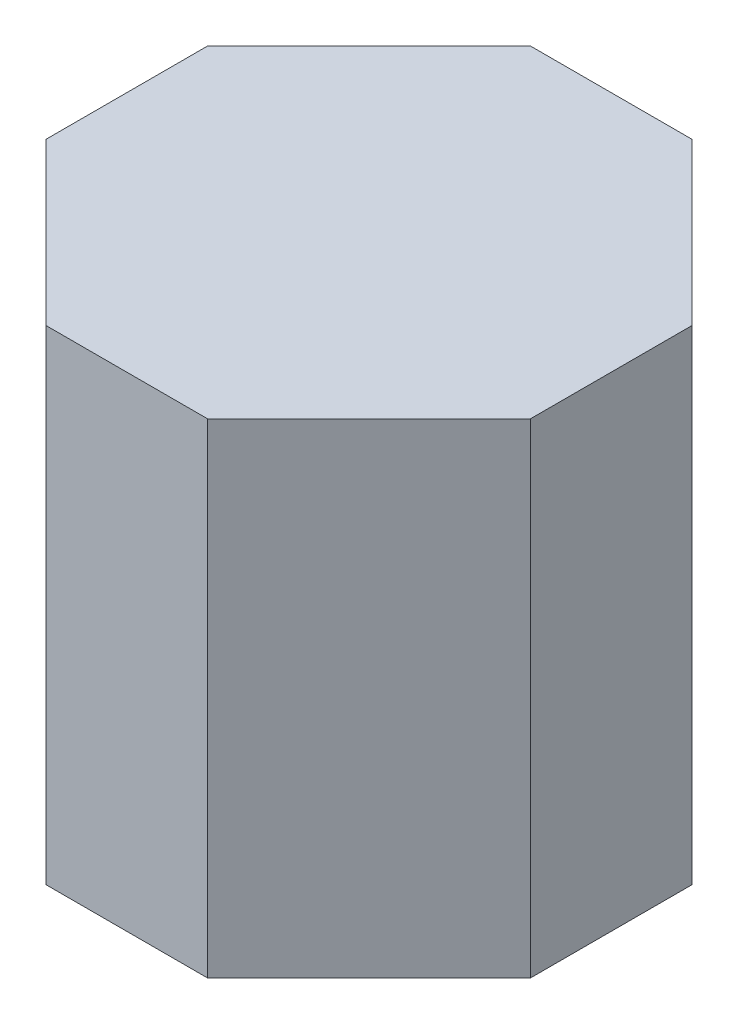
SolidWorks part; units mm, degrees
ref_plane "Plan de face" through (0, 0, 0) normal (0, 0, 1) x (1, 0, 0)
ref_plane "Plan de dessus" through (0, 0, 0) normal (0, 1, 0) x (1, 0, 0)
ref_plane "Plan de droite" through (0, 0, 0) normal (1, 0, 0) x (0, 0, -1)
sketch "Esquisse1" plane through (0, 0, 0) normal (0, 0, 1) x (1, 0, 0)
  line L0 (15, -15) -> (-15, 15) construction
  line L1 (-15, 15) -> (15, 15)
  line L2 (-15, 15) -> (-15, -15)
  line L3 (-15, -15) -> (15, -15)
  line L4 (15, 15) -> (15, -15)
  line L5 (-15, -15) -> (15, 15) construction
  dimension "D1" = 30
  dimension "D2" = 30
extrude "Boss.-Extru.1" add sketch "Esquisse1" along normal blind 30
sketch "Esquisse3" plane through (0, 15, 0) normal (0, 1, 0) x (1, 0, 0)
  line L0 (-15, -20) -> (-5, -30)
  line L1 (-15, -30) -> (-15, 0) construction
  line L2 (15, -30) -> (-15, -30) construction
  line L3 (-15, -20) -> (-15, -30)
  line L4 (-15, -30) -> (-5, -30)
  line L5 (15, 0) -> (-15, -30) construction
  line L6 (-15, 0) -> (15, -30) construction
  line L7 (-15, 0) -> (-15, -10)
  line L8 (-5, 0) -> (-15, -10)
  line L9 (-5, 0) -> (-15, 0)
  line L10 (15, 0) -> (5, 0)
  line L11 (15, -10) -> (5, 0)
  line L12 (15, -10) -> (15, 0)
  line L13 (15, -30) -> (15, -20)
  line L14 (5, -30) -> (15, -20)
  line L15 (5, -30) -> (15, -30)
  point P16 (0, -15)
  point P29 (0, -15)
  dimension "D1" = 45
  dimension "D2" = 10
  dimension "D3" = 4
extrude "Enlèv. mat.-Extru.1" cut sketch "Esquisse3" against normal up to next
sketch "Esquisse4" plane through (-17.5, 0, 17.5) normal (-0.7071, 0, 0.7071) x (0.7071, 0, 0.7071)
  line L0 (3.5355, -15) -> (3.5355, 15) construction
  line L1 (3.5355, -15) -> (17.6777, -15) construction
  circle A0 centre (10.6055, -5) radius 3.25
  point P2 (0, 0)
  point P4 (12.3268, 0)
  point P5 (10.3649, 0)
  point P6 (10.4453, 0)
  point P7 (0, 0)
  point P10 (10.5788, 0)
  point P11 (0, 0)
  point P12 (0, 0)
  point P13 (10.6055, -5.4955)
  dimension "D1" = 6.5
  dimension "D2" = 7.07
  dimension "D3" = 10
extrude "Enlèv. mat.-Extru.2" cut sketch "Esquisse4" against normal up to next
sketch "Esquisse6" plane through (0, -15, 0) normal (0, -1, 0) x (1, 0, 0)
  circle A0 centre (0, 15) radius 2.75
  point P2 (3.58, 15)
  dimension "D1" = 5.5
  dimension "D2" = 5
extrude "Enlèv. mat.-Extru.3" cut sketch "Esquisse6" against normal blind 10 contours A0
